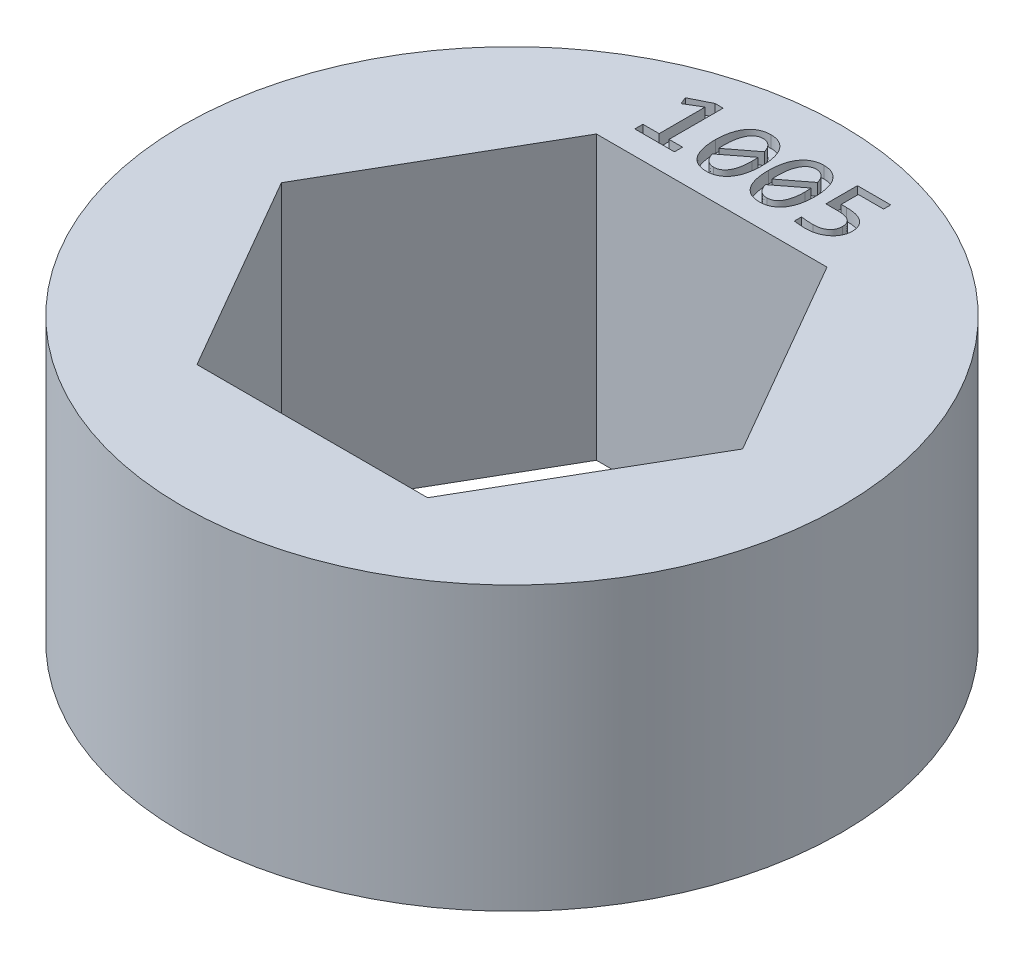
SolidWorks part; units mm, degrees
material "Nylon 101"
ref_plane "Front Plane" through (0, 0, 0) normal (0, 0, 1) x (1, 0, 0)
ref_plane "Top Plane" through (0, 0, 0) normal (0, 1, 0) x (1, 0, 0)
ref_plane "Right Plane" through (0, 0, 0) normal (1, 0, 0) x (0, 0, -1)
sketch "Sketch1" plane through (0, 0, 0) normal (0, 1, 0) x (1, 0, 0)
  line L1 (7.7723, 0) -> (3.8861, 6.731)
  line L2 (3.8861, 6.731) -> (-3.8861, 6.731)
  line L3 (-3.8861, 6.731) -> (-7.7723, 0)
  line L4 (-7.7723, 0) -> (-3.8861, -6.731)
  line L5 (-3.8861, -6.731) -> (3.8861, -6.731)
  line L6 (3.8861, -6.731) -> (7.7723, 0)
  circle A0 centre (0, 0) radius 6.731 construction
  circle A1 centre (0, 0) radius 11.1125
  dimension "D1" = 13.462
  dimension "D2" = 22.225
extrude "Boss-Extrude1" add sketch "Sketch1" along normal blind 9.525
sketch "Sketch2" plane through (0, 9.525, 0) normal (0, 1, 0) x (1, 0, 0)
  line L0 (-4.2615, 7.5247) -> (4.1119, 7.5247) construction
  line L1 (3.8861, 6.731) -> (-3.8861, 6.731) construction
  text T0 "1005" font "Consolas" height in points 8
  dimension "D1" = 0.7937
extrude "Cut-Extrude1" cut sketch "Sketch2" against normal blind 0.4
